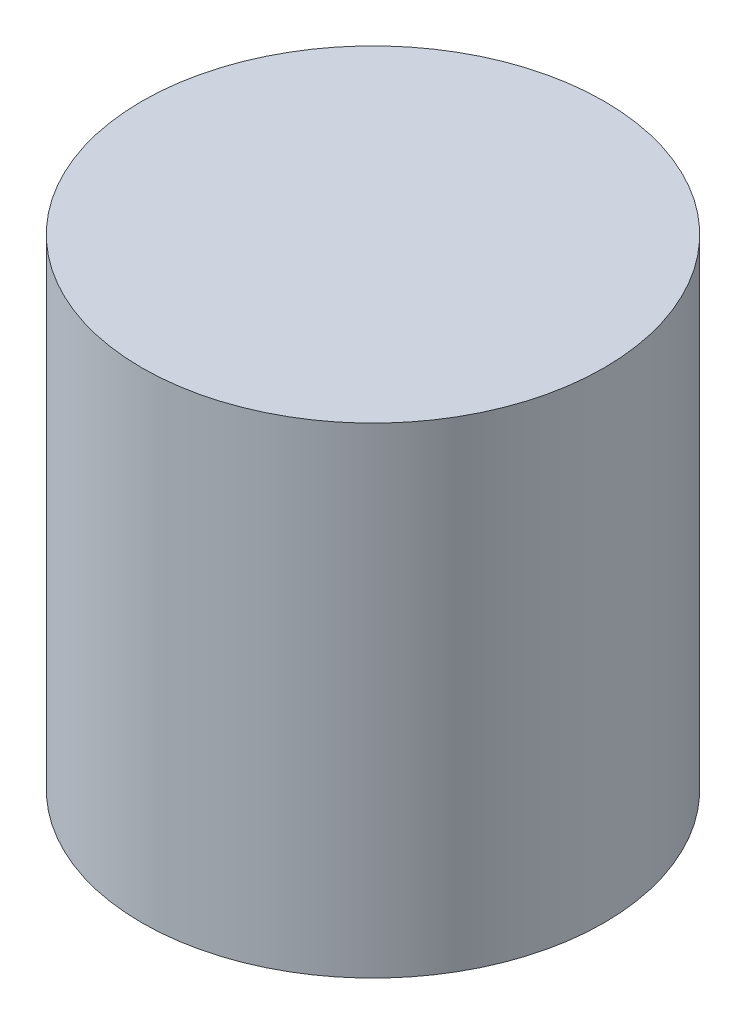
SolidWorks part; units mm, degrees
material "1060-O (SS)"
ref_plane "Front Plane" through (0, 0, 0) normal (0, 0, 1) x (1, 0, 0)
ref_plane "Top Plane" through (0, 0, 0) normal (0, 1, 0) x (1, 0, 0)
ref_plane "Right Plane" through (0, 0, 0) normal (1, 0, 0) x (0, 0, -1)
sketch "Sketch1" plane through (0, 0, 0) normal (0, 1, 0) x (1, 0, 0)
  circle A0 centre (0, 0) radius 24.9
  dimension "D1" = 49.8
extrude "Boss-Extrude1" add sketch "Sketch1" along normal blind 51.8
